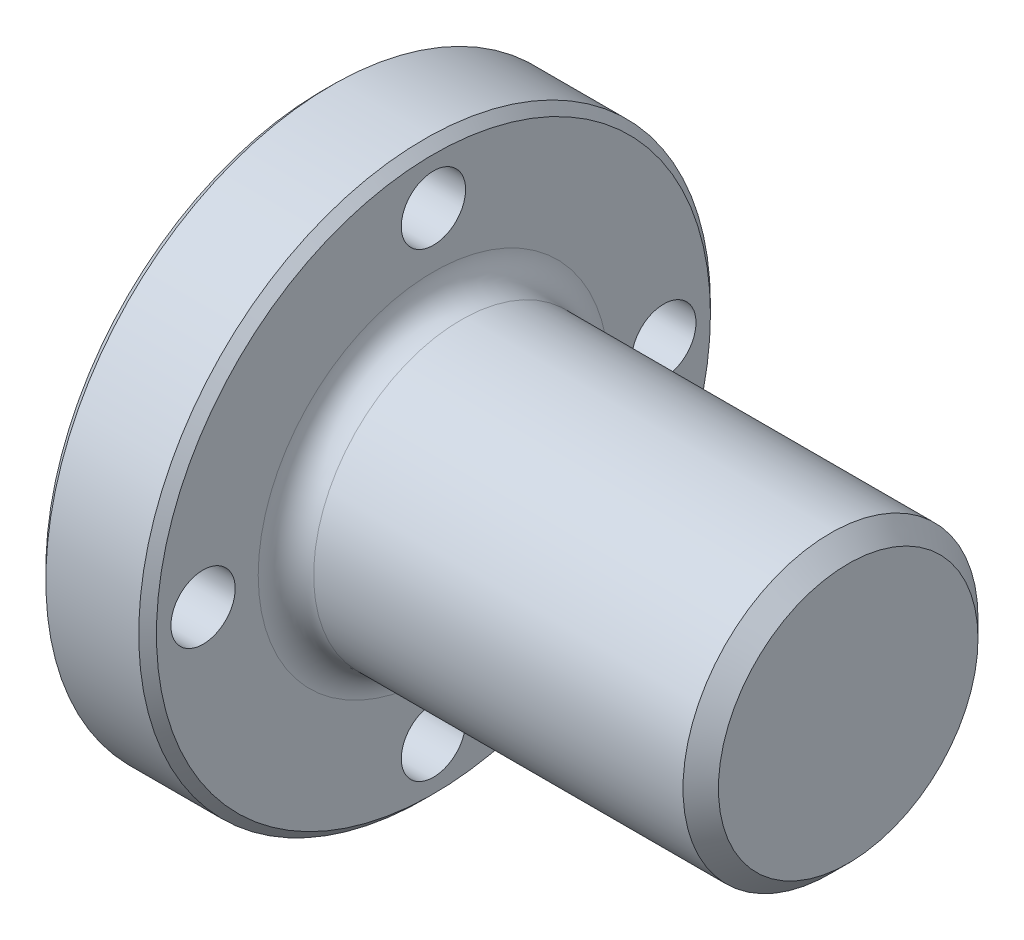
SolidWorks part; units mm, degrees
ref_plane "Front Plane" through (0, 0, 0) normal (1, 0, 0) x (0, 1, 0)
ref_plane "Top Plane" through (0, 0, 0) normal (0, 0, 1) x (0, 1, 0)
ref_plane "Right Plane" through (0, 0, 0) normal (0, 1, 0) x (-1, 0, 0)
sketch "Sketch1" plane through (0, 0, 0) normal (1, 0, 0) x (0, 1, 0)
  circle A0 centre (0, 0) radius 24.6126
extrude "Boss-Extrude1" add sketch "Sketch1" along normal blind 9.525
sketch "Sketch2" plane through (0, 0, 0) normal (1, 0, 0) x (0, 1, 0)
  circle A0 centre (0, 0) radius 12.7
extrude "Boss-Extrude2" add sketch "Sketch2" along normal blind 35.7124 from offset 9.525
sketch "Sketch3" plane through (0, 0, 0) normal (1, 0, 0) x (0, 1, 0)
  circle A0 centre (0, 0) radius 8.7122
extrude "Boss-Extrude4" add sketch "Sketch3" against normal blind 4.826
sketch "Sketch4" plane through (0, 0, 0) normal (1, 0, 0) x (0, 1, 0)
  circle A0 centre (0, 19.8374) radius 2.7686
  circle A1 centre (19.8374, 0) radius 2.7686
  circle A2 centre (0, -19.8374) radius 2.7686
  circle A3 centre (-19.8374, 0) radius 2.7686
extrude "Cut-Extrude2" cut sketch "Sketch4" along normal through all
fillet "Fillet1" radius 0.381 1 edges at (0, 0, -8.7122)
fillet "Fillet2" radius 2.3876 1 edges at (9.525, 0, -12.7)
chamfer "Chamfer1" distance 0.762 angle 45 2 edges at (9.525, 0, -24.6126) (0, 0, -24.6126)
chamfer "Chamfer2" distance 1.524 angle 45 1 edges at (45.2374, 0, -12.7)
